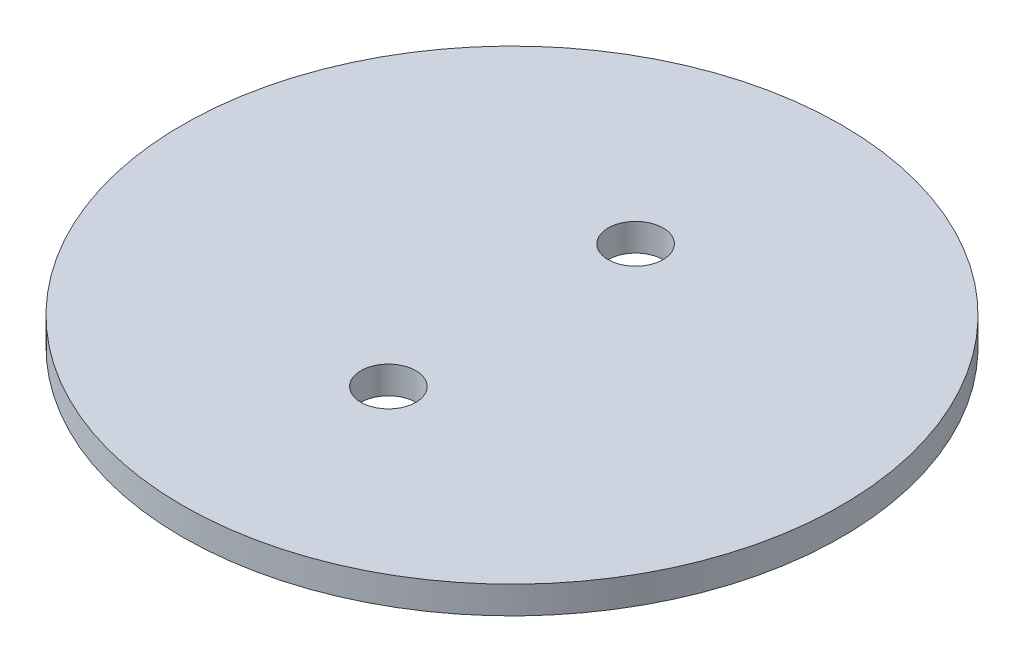
SolidWorks part; units mm, degrees
ref_plane "Front Plane" through (0, 0, 0) normal (0, 0, 1) x (1, 0, 0)
ref_plane "Top Plane" through (0, 0, 0) normal (0, 1, 0) x (1, 0, 0)
ref_plane "Right Plane" through (0, 0, 0) normal (1, 0, 0) x (0, 0, -1)
sketch "Sketch1" plane through (0, 0, 0) normal (0, 1, 0) x (1, 0, 0)
  line L0 (-28.5, 0) -> (28.5, 0) construction
  line L1 (0, 0) -> (0, 13.5)
  line L2 (0, 0) -> (0, -13.5)
  circle A0 centre (0, 0) radius 36
  circle A1 centre (28.5, 0) radius 3 construction
  circle A2 centre (-28.5, 0) radius 3 construction
  circle A3 centre (0, 13.5) radius 3
  circle A4 centre (0, -13.5) radius 3
  circle A5 centre (-28.5, 0) radius 6.25 construction
  circle A6 centre (0, 13.5) radius 12.5 construction
  circle A7 centre (0, -13.5) radius 12.5 construction
  circle A8 centre (28.5, 0) radius 6.25 construction
  point P11 (0, 0)
  dimension "D1" = 72
  dimension "D3" = 6
  dimension "D4" = 13.5
  dimension "D5" = 6
  dimension "D6" = 12.5
  dimension "D7" = 25
  dimension "D2" = 57
extrude "Boss-Extrude1" add sketch "Sketch1" against normal blind 3
